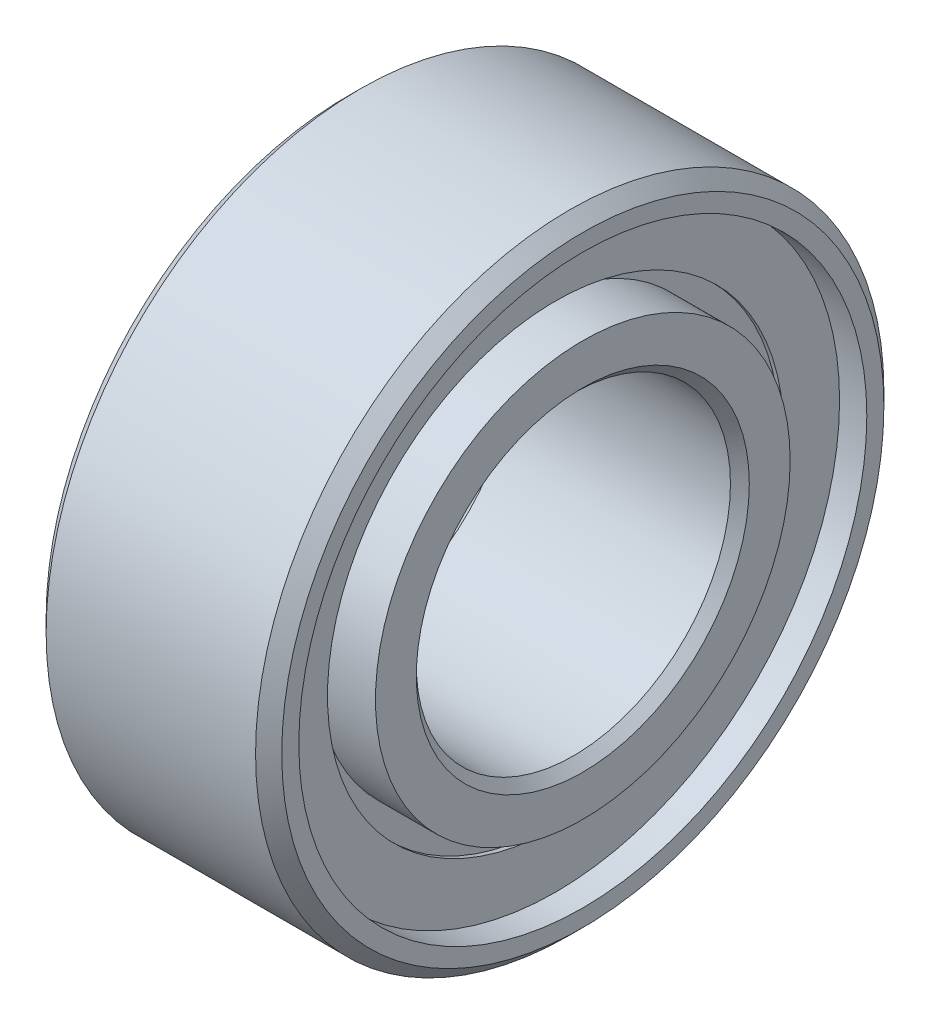
SolidWorks part; units mm, degrees
ref_plane "Front Plane" through (0, 0, 0) normal (0, 0, 1) x (1, 0, 0)
ref_plane "Top Plane" through (0, 0, 0) normal (0, 1, 0) x (1, 0, 0)
ref_plane "Right Plane" through (0, 0, 0) normal (1, 0, 0) x (0, 0, -1)
sketch "Sketch1" plane through (0, 0, 0) normal (0, 0, 1) x (1, 0, 0)
  line L0 (-2.3812, 3.3655) -> (-2.1907, 3.175)
  line L1 (-2.1907, 3.175) -> (2.1907, 3.175)
  line L2 (2.1907, 3.175) -> (2.3812, 3.3655)
  line L3 (2.3812, 3.3655) -> (2.3812, 4.191)
  line L4 (2.3812, 4.191) -> (1.1906, 4.191)
  line L5 (1.1906, 4.191) -> (1.1906, 5.7404)
  line L6 (1.1906, 5.7404) -> (1.7413, 5.7404)
  line L7 (1.7413, 5.7404) -> (1.7413, 4.6101)
  line L8 (1.7413, 4.6101) -> (1.8306, 4.6101)
  line L9 (1.8306, 4.6101) -> (1.8306, 5.7404)
  line L10 (1.8306, 5.7404) -> (2.3812, 5.7404)
  line L11 (2.3812, 5.7404) -> (2.3812, 6.0854)
  line L12 (2.3812, 6.0854) -> (2.1167, 6.35)
  line L13 (2.1167, 6.35) -> (-2.1167, 6.35)
  line L14 (-2.1167, 6.35) -> (-2.3812, 6.0854)
  line L15 (-2.3812, 6.0854) -> (-2.3812, 5.7404)
  line L16 (-2.3812, 5.7404) -> (-1.8306, 5.7404)
  line L17 (-1.8306, 5.7404) -> (-1.8306, 4.6101)
  line L18 (-1.8306, 4.6101) -> (-1.7413, 4.6101)
  line L19 (-1.7413, 4.6101) -> (-1.7413, 5.7404)
  line L20 (-1.7413, 5.7404) -> (-1.1906, 5.7404)
  line L21 (-1.1906, 5.7404) -> (-1.1906, 4.191)
  line L22 (-1.1906, 4.191) -> (-2.3812, 4.191)
  line L23 (-2.3812, 4.191) -> (-2.3812, 3.3655)
  line L24 (-2.3812, 0) -> (2.3812, 0) construction
revolve "Revolve1" add sketch "Sketch1" angle 360 about L24
